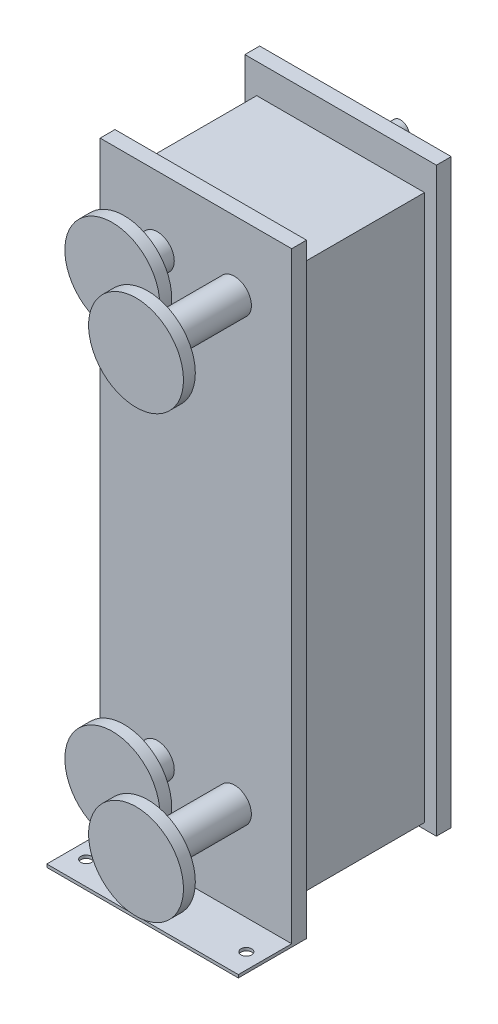
SolidWorks part; units mm, degrees
ref_plane "Front" through (0, 0, 0) normal (0, 0, 1) x (1, 0, 0)
ref_plane "Top" through (0, 0, 0) normal (0, 1, 0) x (1, 0, 0)
ref_plane "Right" through (0, 0, 0) normal (1, 0, 0) x (0, 0, -1)
sketch "Эскиз1" plane through (0, 0, 0) normal (0, 0, 1) x (1, 0, 0)
  line L1 (-161.5, 510) -> (161.5, 510)
  line L2 (-161.5, 510) -> (-161.5, -510)
  line L3 (-161.5, -510) -> (161.5, -510)
  line L4 (161.5, 510) -> (161.5, -510)
  line L5 (-161.5, 510) -> (161.5, -510) construction
  line L6 (-161.5, -510) -> (161.5, 510) construction
  point P0 (0, 0)
  dimension "D1" = 323
  dimension "D2" = 1020
extrude "Вытянуть1" add sketch "Эскиз1" along normal blind 25
ref_plane "Плоскость1" through (0, 0, -219) normal (0, 0, -1) x (-1, 0, 0)
sketch "Эскиз3" plane through (0, 0, -219) normal (0, 0, -1) x (-1, 0, 0)
  line L0 (161.5, 510) -> (161.5, -510) construction
  line L1 (-161.5, 510) -> (161.5, 510)
  line L2 (-161.5, 510) -> (-161.5, -470)
  line L3 (-161.5, -470) -> (161.5, -470)
  line L4 (161.5, 510) -> (161.5, -470)
  line L5 (161.5, -510) -> (-161.5, -510) construction
  dimension "D1" = 40
extrude "Вытянуть2" add sketch "Эскиз3" along normal blind 25
sketch "Эскиз15" plane through (0, 0, 0) normal (0, 0, -1) x (-1, 0, 0)
  line L0 (-161.5, 510) -> (161.5, 510) construction
  line L1 (141.5, 460) -> (-141.5, 460)
  line L2 (141.5, 460) -> (141.5, -460)
  line L3 (141.5, -460) -> (-141.5, -460)
  line L4 (-141.5, 460) -> (-141.5, -460)
  line L5 (141.5, 460) -> (-141.5, -460) construction
  line L6 (141.5, -460) -> (-141.5, 460) construction
  line L7 (161.5, 510) -> (161.5, -510) construction
  point P0 (0, 0)
  dimension "D1" = 50
  dimension "D2" = 20
sketch "Эскиз17" plane through (0, 0, 25) normal (0, 0, 1) x (1, 0, 0)
  line L0 (0, 393) -> (0, 510) construction
  line L1 (-65, 393) -> (65, 393) construction
  line L5 (-65, 393) -> (-65, -350) construction
  line L6 (-65, -350) -> (65, -350) construction
  line L7 (65, 393) -> (65, -350) construction
  line L8 (161.5, 510) -> (-161.5, 510) construction
  line L9 (-161.5, -510) -> (161.5, -510) construction
  circle A0 centre (-65, -350) radius 28.5
  circle A1 centre (65, -350) radius 28.5
  circle A2 centre (-65, 393) radius 28.5
  circle A3 centre (65, 393) radius 28.5
  dimension "D1" = 57
  dimension "D4" = 160
  dimension "D2" = 130
  dimension "D3" = 743
extrude "Extrude3" add sketch "Эскиз15" along normal up to surface (219 mm away) up to face at (0, 20, -219)
sketch "Sketch3" plane through (0, -510, 0) normal (0, -1, 0) x (1, 0, 0)
  line L0 (0, 221.3158) -> (0, -380) construction
  line L1 (-161.5, 25) -> (161.5, 25)
  line L2 (-161.5, 25) -> (-161.5, 115)
  line L3 (-161.5, 115) -> (161.5, 115)
  line L4 (161.5, 25) -> (161.5, 115)
  line L5 (-17, -330) -> (17, -380) construction
  line L6 (-17, -380) -> (17, -380)
  line L7 (-17, -380) -> (-17, -330)
  line L8 (-17, -330) -> (17, -330)
  line L9 (17, -380) -> (17, -330)
  line L10 (-17, -380) -> (17, -330) construction
  line L11 (-135, 75) -> (0, 75) construction
  line L12 (0, 75) -> (135, 75) construction
  circle A0 centre (0, -355) radius 9
  circle A1 centre (-135, 75) radius 9
  circle A2 centre (135, 75) radius 9
  dimension "D4" = 270
  dimension "D5" = 18
  dimension "D8" = 18
  dimension "D9" = 25
  dimension "D1" = 90
  dimension "D2" = 34
  dimension "D3" = 50
  dimension "D6" = 40
  dimension "D7" = 430
extrude "Extrude6" add sketch "Sketch3" against normal blind 5
sketch "Sketch4" plane through (0, 0, -330) normal (0, 0, 1) x (1, 0, 0)
  line L1 (-17, -510) -> (17, -510)
  line L2 (-17, -510) -> (-17, -405)
  line L3 (-17, -405) -> (17, -405)
  line L4 (17, -510) -> (17, -405)
  dimension "D1" = 105
extrude "Extrude7" add sketch "Sketch4" along normal blind 10
sketch "Sketch5" plane through (0, 0, -244) normal (0, 0, -1) x (-1, 0, 0)
  line L0 (0, 550.099) -> (0, -710.8326) construction
  line L1 (161.5, 510) -> (-161.5, 510) construction
  line L2 (-161.5, -470) -> (161.5, -470) construction
  circle A0 centre (0, -420) radius 15
  circle A1 centre (0, 430) radius 15
  dimension "D1" = 80
  dimension "D2" = 50
  dimension "D3" = 30
extrude "Extrude8" add sketch "Sketch5" along normal up to surface (76 mm away) up to face at (0, -457.5, -320)
extrude "Бобышка-Вытянуть1" add sketch "Эскиз17" along normal blind 76
sketch "Эскиз18" plane through (0, 0, 101) normal (0, 0, 1) x (1, 0, 0)
  circle A0 centre (-65, 393) radius 80
  circle A1 centre (-65, -350) radius 80
  dimension "D1" = 160
  dimension "D2" = 160
extrude "Бобышка-Вытянуть2" add sketch "Эскиз18" against normal blind 20
sketch "Эскиз19" plane through (0, 0, 101) normal (0, 0, 1) x (1, 0, 0)
  circle A0 centre (65, 393) radius 28.5
  circle A1 centre (65, -350) radius 28.5
  dimension "D1" = 57
  dimension "D2" = 57
extrude "Бобышка-Вытянуть3" add sketch "Эскиз19" along normal blind 90
sketch "Эскиз20" plane through (0, 0, 191) normal (0, 0, 1) x (1, 0, 0)
  circle A0 centre (65, 393) radius 80
  circle A1 centre (65, -350) radius 80
  dimension "D1" = 160
  dimension "D2" = 160
extrude "Бобышка-Вытянуть4" add sketch "Эскиз20" against normal blind 20
ref_plane "Плоскость2" through (0, 0, 0) normal (1, 0, 0) x (0, 0, -1)
